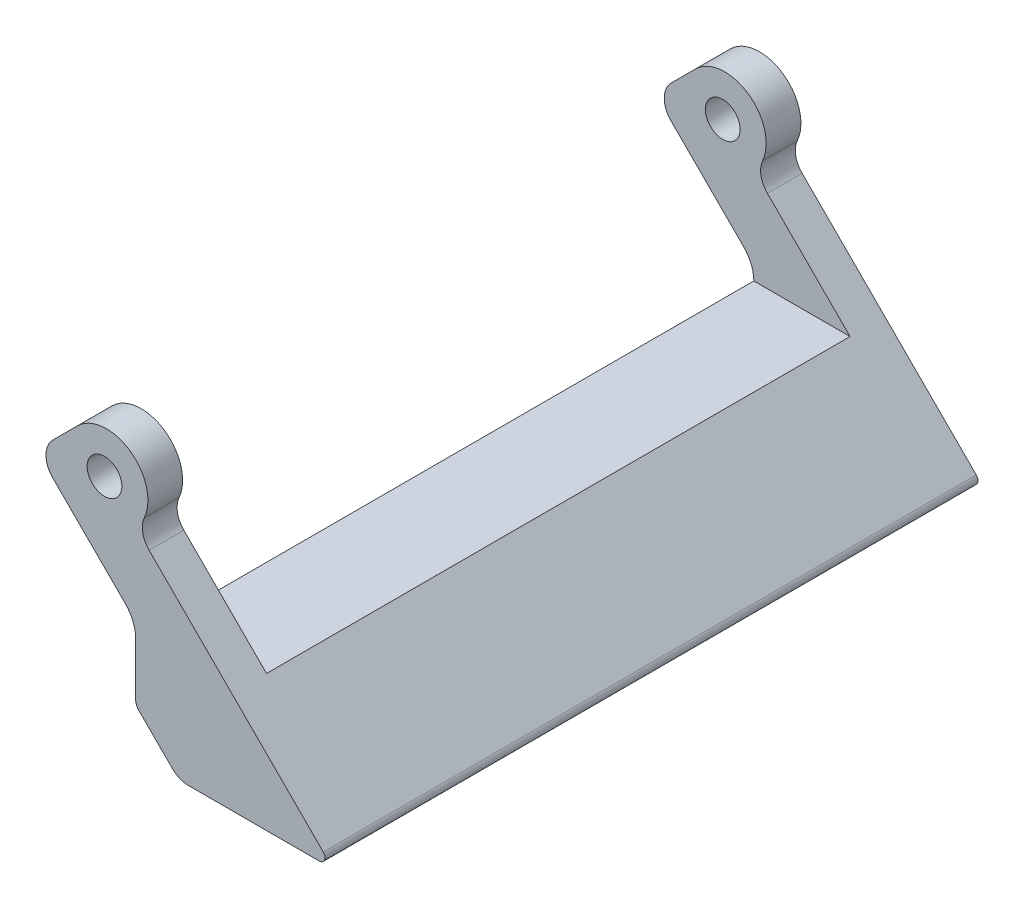
SolidWorks part; units mm, degrees
material "1060-H12"
ref_plane "Front Plane" through (0, 0, 0) normal (0, 0, 1) x (1, 0, 0)
ref_plane "Top Plane" through (0, 0, 0) normal (0, 1, 0) x (1, 0, 0)
ref_plane "Right Plane" through (0, 0, 0) normal (1, 0, 0) x (0, 0, -1)
sketch "Sketch1" plane through (0, 0, 0) normal (0, 0, 1) x (1, 0, 0)
  line L0 (30.0967, -21) -> (76.9648, -21)
  line L1 (3.6822, -19.5) -> (18.5462, -19.5)
  line L2 (-9.1152, 9.3685) -> (-2.3482, 2.6015)
  line L6 (-2.3482, 2.6015) -> (-4.4696, 0.4802)
  line L7 (-4.4696, -2.3482) -> (1.8035, -8.6213)
  line L8 (2.6822, -10.7426) -> (2.6822, -18.5)
  line L9 (3.8542, -3.6009) -> (18.8997, -18.6464)
  circle A0 centre (0, 0) radius 1.5
  circle A1 centre (30.0967, 0.35) radius 21.35
  arc A2 (-2.3482, 2.6015) -> (3.4407, -1.3744) centre (0.1771, 0.0761) cw
  arc A3 (3.4407, -1.3744) -> (3.8542, -3.6009) centre (5.2684, -2.1867) ccw
  arc A4 (2.6822, -18.5) -> (3.6822, -19.5) centre (3.6822, -18.5) ccw
  arc A6 (-4.4696, 0.4802) -> (-4.4696, -2.3482) centre (-3.0553, -0.934) ccw
  arc A7 (18.5462, -19.5) -> (18.8997, -18.6464) centre (18.5462, -19) ccw
  arc A8 (1.8035, -8.6213) -> (2.6822, -10.7426) centre (-0.3178, -10.7426) cw
  point P10 (15, -14.7467)
  point P23 (2.6822, -19.5)
  point P26 (2.6015, -2.3482)
  point P33 (2.6822, -9.5)
  dimension "D1" = 3
  dimension "D4" = 42.7
  dimension "D13" = 1
  dimension "D14" = 2
  dimension "D15" = 0.5
  dimension "D16" = 3
  dimension "D7" = 2
  dimension "D2" = 21
  dimension "D3" = 1.5
  dimension "D5" = 45
  dimension "D6" = 15
  dimension "D9" = 10
  dimension "D10" = 5
extrude "Boss-Extrude1" add sketch "Sketch1" along normal blind 3
sketch "Sketch2" plane through (0, 0, 3) normal (0, 0, 1) x (1, 0, 0)
  line L0 (3.8542, -3.6009) -> (18.8997, -18.6464) construction
  line L1 (3.6822, -19.5) -> (18.5462, -19.5) construction
  line L2 (2.6822, -10.7426) -> (2.6822, -18.5) construction
  line L3 (3.8542, -3.6009) -> (18.8997, -18.6464)
  line L4 (3.6822, -19.5) -> (18.5462, -19.5)
  line L5 (2.6822, -10.7426) -> (2.6822, -18.5)
  line L6 (2.6822, -10.7426) -> (10.9959, -10.7426)
  arc A0 (18.5462, -19.5) -> (18.8997, -18.6464) centre (18.5462, -19) ccw construction
  arc A1 (2.6822, -18.5) -> (3.6822, -19.5) centre (3.6822, -18.5) ccw construction
  arc A2 (18.5462, -19.5) -> (18.8997, -18.6464) centre (18.5462, -19) ccw
  arc A3 (2.6822, -18.5) -> (3.6822, -19.5) centre (3.6822, -18.5) ccw
  line M4 (2.6822, -10.7426) -> (2.6822, -18.5)
  arc M5 (2.6822, -18.5) -> (3.6822, -19.5) centre (3.6822, -18.5) ccw
  line M6 (3.6822, -19.5) -> (18.5462, -19.5)
  arc M7 (18.5462, -19.5) -> (18.8997, -18.6464) centre (18.5462, -19) ccw
  line M8 (18.8997, -18.6464) -> (3.8542, -3.6009)
extrude "Boss-Extrude2" add sketch "Sketch2" along normal blind 25.2 contours L6 M4 M5 M6 M7 M8
mirror "Mirror1" about plane through (0, 0, 28.2) normal (0, 0, 1) of "Boss-Extrude1", "Boss-Extrude2"
sketch "Sketch3" plane through (2.6822, 0, 0) normal (-1, 0, 0) x (0, 0, 1)
  line L0 (0, -15.7426) -> (56.4, -15.7426)
  line L1 (0, -10.7426) -> (0, -18.5) construction
  line L2 (56.4, -10.7426) -> (56.4, -18.5) construction
  line L3 (53.4, -10.7426) -> (3, -10.7426) construction
  dimension "D1" = 5
ref_plane "Plane1" through (-6.5302, -6.5302, 0) normal (-0.7071, -0.7071, 0) x (0, 0, 1)
sketch "Sketch6" plane through (-6.5302, -6.5302, 0) normal (-0.7071, -0.7071, 0) x (0, 0, 1)
  line L1 (56.4, -13.0283) -> (-1.1366, -13.0283)
  line L2 (56.4, -13.0283) -> (56.4, -22.1438)
  line L3 (56.4, -22.1438) -> (-1.1366, -22.1438)
  line L4 (-1.1366, -13.0283) -> (-1.1366, -22.1438)
extrude "Cut-Extrude1" cut sketch "Sketch6" along normal through all
fillet "Fillet1" radius 2 1 edges at (6.4396, -19.5, 28.2)
fillet "Fillet2" radius 1 1 edges at (2.6822, -15.7426, 28.2)
